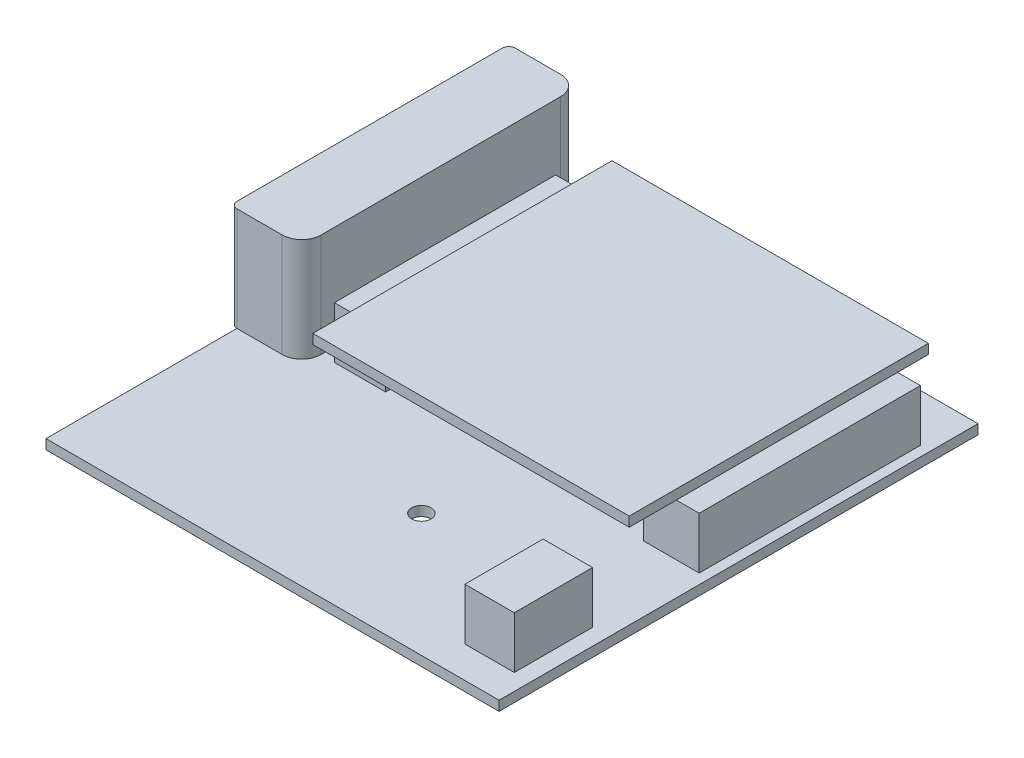
SolidWorks part; units mm, degrees
ref_plane "前视基准面" through (0, 0, 0) normal (0, 0, 1) x (1, 0, 0)
ref_plane "上视基准面" through (0, 0, 0) normal (0, 1, 0) x (1, 0, 0)
ref_plane "右视基准面" through (0, 0, 0) normal (1, 0, 0) x (0, 0, -1)
sketch "草图1" plane through (0, 0, 0) normal (0, 1, 0) x (1, 0, 0)
  line L1 (35, -37) -> (-35, -37)
  line L2 (35, -37) -> (35, 37)
  line L3 (35, 37) -> (-35, 37)
  line L4 (-35, -37) -> (-35, 37)
  line L5 (35, -37) -> (-35, 37) construction
  line L6 (35, 37) -> (-35, -37) construction
  circle A0 centre (4, 22) radius 1.5
  circle A1 centre (-12, 2) radius 1.5
  circle A2 centre (20, 2) radius 1.5
  circle A3 centre (4, -18) radius 1.5
  point P0 (0, 0)
  dimension "D3" = 3
  dimension "D4" = 3
  dimension "D5" = 3
  dimension "D6" = 3
  dimension "D1" = 70
  dimension "D2" = 74
  dimension "D7" = 19
  dimension "D8" = 59
  dimension "D9" = 39
  dimension "D10" = 39
  dimension "D11" = 23
  dimension "D12" = 32
extrude "凸台-拉伸1" add sketch "草图1" along normal blind 1.5
sketch "草图2" plane through (0, 1.5, 0) normal (0, 1, 0) x (1, 0, 0)
  line L6 (35, 37) -> (-35, 37) construction
  line L7 (-35, 35.5) -> (-28, 35.5)
  line L8 (-36, 34.5) -> (-36, -6.5)
  line L9 (-35, -7.5) -> (-28, -7.5)
  line L10 (-25, 32.5) -> (-25, -4.5)
  line L11 (-35, 37) -> (-35, -37) construction
  arc A4 (-28, -7.5) -> (-25, -4.5) centre (-28, -4.5) ccw
  arc A5 (-25, 32.5) -> (-28, 35.5) centre (-28, 32.5) ccw
  arc A6 (-36, -6.5) -> (-35, -7.5) centre (-35, -6.5) ccw
  arc A7 (-36, 34.5) -> (-35, 35.5) centre (-35, 34.5) cw
  dimension "D4" = 1
  dimension "D5" = 3
  dimension "D6" = 1
  dimension "D1" = 1.5
  dimension "D2" = 11
  dimension "D3" = 43
extrude "凸台-拉伸2" add sketch "草图2" along normal blind 16 contours A4 L10 A5 L7 A7 L8 A6 L9
sketch "草图3" plane through (0, 1.5, 0) normal (0, 1, 0) x (1, 0, 0)
  line L1 (-22.9137, 29.6529) -> (-15.0118, 29.6529)
  line L2 (-22.9137, 29.6529) -> (-22.9137, -4.5266)
  line L3 (-22.9137, -4.5266) -> (-15.0118, -4.5266)
  line L4 (-15.0118, 29.6529) -> (-15.0118, -4.5266)
  line L5 (24.834, -4.5266) -> (33.4448, -4.5266)
  line L6 (24.834, -4.5266) -> (24.834, 29.6529)
  line L7 (24.834, 29.6529) -> (33.4448, 29.6529)
  line L8 (33.4448, -4.5266) -> (33.4448, 29.6529)
  line L12 (32.4741, -32.1216) -> (24.8391, -32.1216)
  line L13 (32.4741, -32.1216) -> (32.4741, -20.0315)
  line L14 (32.4741, -20.0315) -> (24.8391, -20.0315)
  line L15 (24.8391, -32.1216) -> (24.8391, -20.0315)
extrude "凸台-拉伸3" add sketch "草图3" along normal blind 8
sketch "草图4" plane through (0, 9.5, 0) normal (0, 1, 0) x (1, 0, 0)
  line L1 (-18.9627, 34.4152) -> (29.917, 34.4152)
  line L2 (-18.9627, 34.4152) -> (-18.9627, -11.8025)
  line L3 (-18.9627, -11.8025) -> (29.917, -11.8025)
  line L4 (29.917, 34.4152) -> (29.917, -11.8025)
extrude "凸台-拉伸4" add sketch "草图4" along normal blind 1.5
